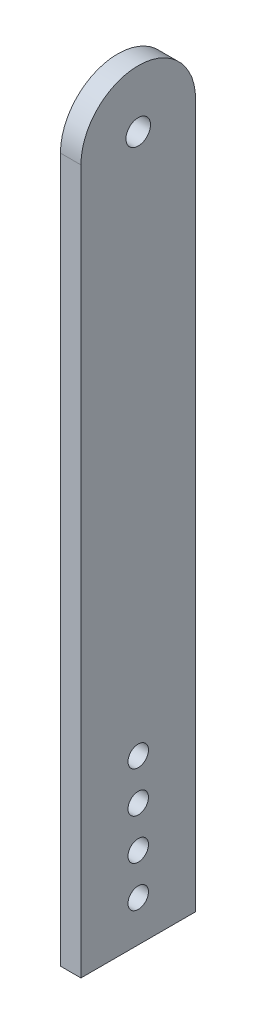
SolidWorks part; units mm, degrees
material "Acrylic (Medium-high impact)"
ref_plane "Ground" through (0, 0, 0) normal (0, 0, 1) x (1, 0, 0)
ref_plane "Right" through (0, 0, 0) normal (0, 1, 0) x (1, 0, 0)
ref_plane "Front" through (0, 0, 0) normal (1, 0, 0) x (0, 0, -1)
sketch "Sketch1" plane through (0, 0, 0) normal (1, 0, 0) x (0, 0, -1)
  line L0 (0, 0) -> (0, 3) construction
  line L1 (-7, 10) -> (-7, 96)
  line L2 (7, 10) -> (7, 96)
  line L3 (-7, 10) -> (7, 10)
  line L4 (0, 10) -> (0, 96) construction
  arc A1 (7, 96) -> (-7, 96) centre (0, 96) ccw
  circle A3 centre (0, 96) radius 1.5
  circle A4 centre (0, 15) radius 1.25
  circle A5 centre (0, 20) radius 1.25
  circle A6 centre (0, 25) radius 1.25
  circle A7 centre (0, 30) radius 1.25
  point P3 (0, 48)
  dimension "D5" = 2.5
  dimension "D1" = 96
  dimension "D6" = 15
  dimension "D8" = 5
  dimension "D7" = 4
extrude "Boss-Extrude1" add sketch "Sketch1" along normal blind 2.5
